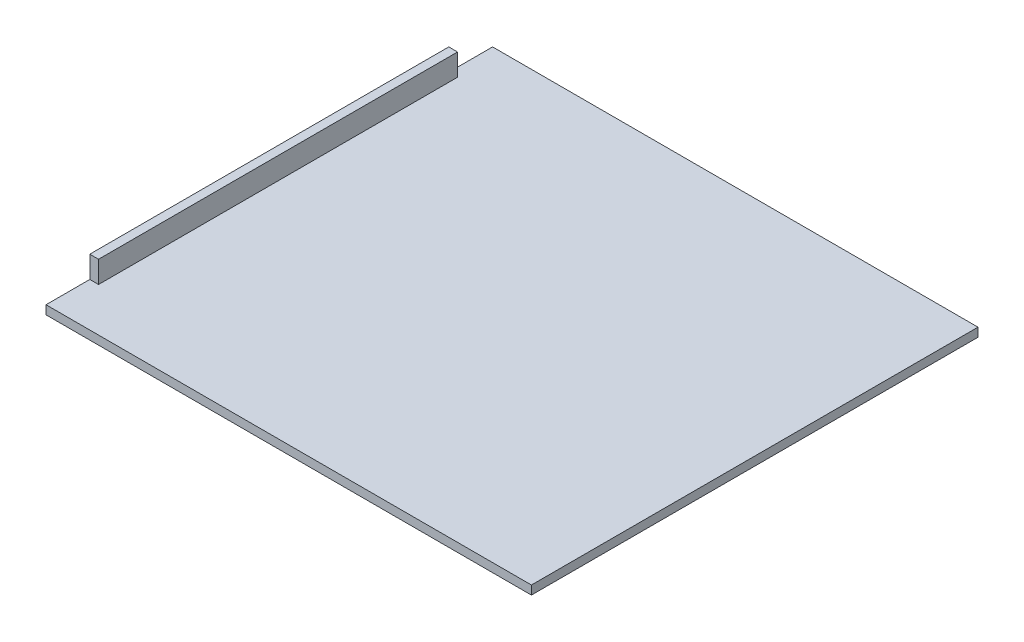
SolidWorks part; units mm, degrees
ref_plane "정면" through (0, 0, 0) normal (0, 0, 1) x (1, 0, 0)
ref_plane "윗면" through (0, 0, 0) normal (0, 1, 0) x (1, 0, 0)
ref_plane "우측면" through (0, 0, 0) normal (1, 0, 0) x (0, 0, -1)
sketch "스케치1" plane through (0, 0, 0) normal (0, 1, 0) x (1, 0, 0)
  line L1 (-55.435, 51) -> (55.435, 51)
  line L2 (-55.435, 51) -> (-55.435, -51)
  line L3 (-55.435, -51) -> (55.435, -51)
  line L4 (55.435, 51) -> (55.435, -51)
  line L5 (-55.435, 51) -> (55.435, -51) construction
  line L6 (-55.435, -51) -> (55.435, 51) construction
  point P0 (0, 0)
  dimension "D1" = 110.87
  dimension "D2" = 102
extrude "보스-돌출1" add sketch "스케치1" along normal blind 2
sketch "스케치2" plane through (0, 2, 0) normal (0, 1, 0) x (1, 0, 0)
  line L5 (-55.435, 51) -> (-55.435, -51) construction
  line L6 (-55.435, 41) -> (-53.435, 41)
  line L7 (-55.435, 41) -> (-55.435, -41)
  line L8 (-55.435, -41) -> (-53.435, -41)
  line L9 (-53.435, 41) -> (-53.435, -41)
  line L10 (55.435, 51) -> (-55.435, 51) construction
  line L11 (-55.435, -51) -> (55.435, -51) construction
  dimension "D1" = 2
  dimension "D2" = 10
  dimension "D3" = 10
extrude "보스-돌출2" add sketch "스케치2" along normal blind 5
